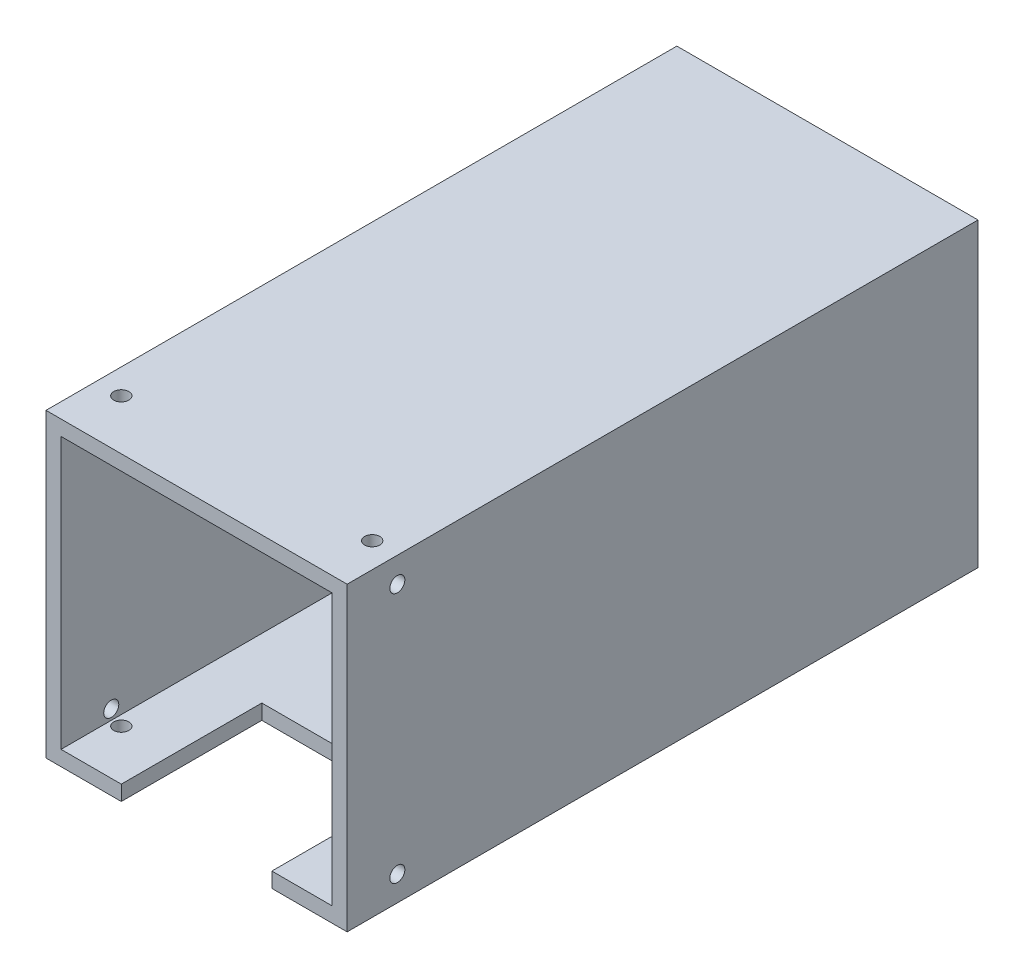
SolidWorks part; units mm, degrees
ref_plane "Front Plane" through (0, 0, 0) normal (0, 0, 1) x (1, 0, 0)
ref_plane "Top Plane" through (0, 0, 0) normal (0, 1, 0) x (1, 0, 0)
ref_plane "Right Plane" through (0, 0, 0) normal (1, 0, 0) x (0, 0, -1)
sketch "Sketch1" plane through (0, 0, 0) normal (0, 0, 1) x (1, 0, 0)
  line L0 (-18.0519, -15.1079) -> (-0.0519, -15.1079)
  line L1 (-39.0112, 23.874) -> (20.9888, 23.874)
  line L2 (-39.0112, 23.874) -> (-39.0112, -36.126)
  line L3 (-39.0112, -36.126) -> (20.9888, -36.126)
  line L4 (20.9888, 23.874) -> (20.9888, -36.126)
  line L5 (-17.9955, 2.8921) -> (-18.0519, -15.1079)
  line L6 (-17.9955, 2.8921) -> (0.0045, 2.8921)
  circle A0 centre (-9.0112, -6.126) radius 9
  circle A1 centre (-17.9955, 2.8921) radius 1.5
  circle A2 centre (-18.0519, -15.1079) radius 1.5
  circle A3 centre (0.0045, 2.8921) radius 1.5
  circle A4 centre (-0.0519, -15.1079) radius 1.5
  arc A5 (0.0045, 2.8921) -> (-0.0519, -15.1079) centre (-2873.2155, 2.8921) cw
  dimension "D3" = 30
  dimension "D5" = 18
  dimension "D1" = 60
  dimension "D2" = 60
  dimension "D4" = 30
  dimension "D6" = 18
  dimension "D7" = 18
  dimension "D8" = 18
  dimension "D9" = 18
  dimension "D10" = 18
extrude "Boss-Extrude1" add sketch "Sketch1" along normal blind 4 contours L4 L1 L2 L3 A3 A5 A4 L0 A2 L5 A1 L6 A0 | A5 A3 L6 A0 A1 L5 A2 L0 A4
sketch "Sketch4" plane through (0, 0, 0) normal (0, 0, -1) x (-1, 0, 0)
  circle A0 centre (9.0112, -6.126) radius 17.3205
  circle A1 centre (-5.8035, 2.8475) radius 2.7
  circle A2 centre (24.1898, 2.2172) radius 2.7
  circle A3 centre (8.6472, -23.4427) radius 2.7
  circle A4 centre (-5.8035, 2.8475) radius 3.2
  circle A5 centre (24.1898, 2.2172) radius 3.2
  circle A6 centre (8.6472, -23.4427) radius 3.2
  dimension "D1" = 5.4
  dimension "D2" = 5.4
  dimension "D3" = 5.4
  dimension "D4" = 30
  dimension "D5" = 30
  dimension "D6" = 30
extrude "Boss-Extrude6" add sketch "Sketch4" along normal blind 34 contours A0 A4 A1 | A0 A4 A1 | A0 A6 A3 | A0 A6 A3 | A2 | A5
sketch "Sketch5" plane through (0, 0, 4) normal (0, 0, 1) x (1, 0, 0)
  line L1 (-39.0112, 23.874) -> (20.9888, 23.874)
  line L2 (-39.0112, 23.874) -> (-39.0112, -36.126)
  line L3 (-39.0112, -36.126) -> (20.9888, -36.126)
  line L4 (20.9888, 23.874) -> (20.9888, -36.126)
  line L5 (-36.0112, 20.874) -> (17.9888, 20.874)
  line L6 (-36.0112, 20.874) -> (-36.0112, -33.126)
  line L7 (-36.0112, -33.126) -> (17.9888, -33.126)
  line L8 (17.9888, 20.874) -> (17.9888, -33.126)
  dimension "D1" = 3
  dimension "D2" = 3
  dimension "D3" = 3
  dimension "D4" = 3
extrude "Boss-Extrude7" add sketch "Sketch5" along normal blind 121.7
sketch "Sketch7" plane through (0, -36.126, 0) normal (0, -1, 0) x (1, 0, 0)
  line L0 (-39.0112, 125.7) -> (20.9888, 125.7) construction
  line L1 (-24.0112, 125.7) -> (5.9888, 125.7)
  line L2 (-24.0112, 125.7) -> (-24.0112, 97.7)
  line L3 (-24.0112, 97.7) -> (5.9888, 97.7)
  line L4 (5.9888, 125.7) -> (5.9888, 97.7)
  line L5 (20.9888, 125.7) -> (20.9888, 0) construction
  line L6 (-39.0112, 125.7) -> (-39.0112, 0) construction
  dimension "D1" = 28
  dimension "D2" = 30
  dimension "D3" = 15
  dimension "D4" = 15
extrude "Cut-Extrude1" cut sketch "Sketch7" against normal blind 30.7
sketch "Sketch15" plane through (0, -36.126, 0) normal (0, -1, 0) x (1, 0, 0)
  circle A0 centre (-34.0112, 115.7) radius 1.5
  circle A1 centre (15.9888, 115.7) radius 1.5
extrude "Cut-Extrude8" cut sketch "Sketch15" against normal blind 82
sketch "Sketch17" plane through (0, 0, 4) normal (0, 0, 1) x (1, 0, 0)
  line L1 (-36.0112, 20.874) -> (17.9888, 20.874)
  line L2 (-36.0112, 20.874) -> (-36.0112, -33.126)
  line L3 (-36.0112, -33.126) -> (17.9888, -33.126)
  line L4 (17.9888, 20.874) -> (17.9888, -33.126)
extrude "Cut-Extrude9" cut sketch "Sketch17" against normal blind 38
sketch "Sketch19" plane through (-39.0112, 0, 0) normal (-1, 0, 0) x (0, 0, 1)
  line L9 (125.7, 23.874) -> (125.7, -36.126) construction
  circle A0 centre (115.7, 18.874) radius 1.5
  circle A1 centre (115.7, -31.126) radius 1.5
  dimension "D1" = 10
  dimension "D2" = 10
extrude "Cut-Extrude10" cut sketch "Sketch19" against normal blind 84
sketch "Sketch20" plane through (0, 0, 0) normal (0, 0, -1) x (-1, 0, 0)
  line L21 (-20.9888, -36.126) -> (-5.9888, -36.126)
  line L22 (-20.9888, -36.126) -> (-20.9888, -21.126)
  line L23 (-20.9888, -21.126) -> (-5.9888, -21.126)
  line L24 (-5.9888, -36.126) -> (-5.9888, -21.126)
  line L25 (39.0112, -36.126) -> (24.0112, -36.126)
  line L26 (39.0112, -36.126) -> (39.0112, -21.126)
  line L27 (39.0112, -21.126) -> (24.0112, -21.126)
  line L28 (24.0112, -36.126) -> (24.0112, -21.126)
  line L29 (39.0112, 23.874) -> (24.0112, 23.874)
  line L30 (39.0112, 23.874) -> (39.0112, 8.874)
  line L31 (39.0112, 8.874) -> (24.0112, 8.874)
  line L32 (24.0112, 23.874) -> (24.0112, 8.874)
  line L33 (-20.9888, 23.874) -> (-5.9888, 23.874)
  line L34 (-20.9888, 23.874) -> (-20.9888, 8.874)
  line L35 (-20.9888, 8.874) -> (-5.9888, 8.874)
  line L36 (-5.9888, 23.874) -> (-5.9888, 8.874)
  circle A4 centre (-13.4888, 16.374) radius 1.5
  circle A5 centre (-13.4888, -28.626) radius 1.5
  circle A6 centre (31.5112, -28.626) radius 1.5
  circle A7 centre (31.5112, 16.374) radius 1.5
  dimension "D1" = 15
  dimension "D2" = 15
  dimension "D3" = 15
  dimension "D4" = 15
  dimension "D5" = 15
  dimension "D6" = 15
  dimension "D7" = 15
  dimension "D8" = 15
extrude "Boss-Extrude8" add sketch "Sketch20" against normal blind 5
